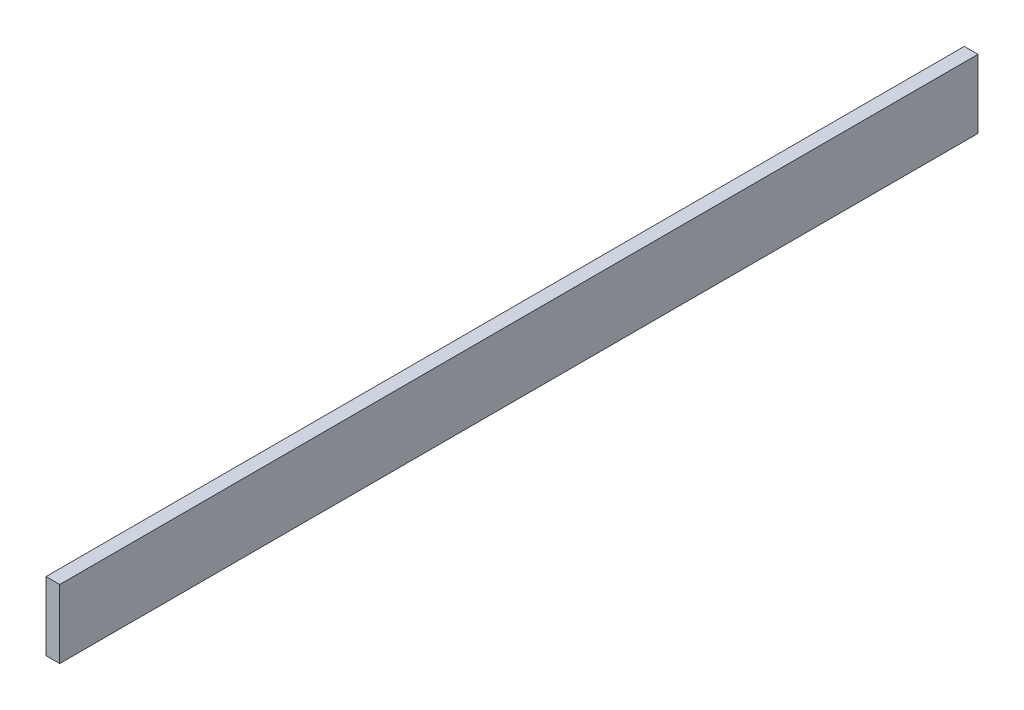
SolidWorks part; units mm, degrees
ref_plane "前视基准面" through (0, 0, 0) normal (0, 0, 1) x (1, 0, 0)
ref_plane "上视基准面" through (0, 0, 0) normal (0, 1, 0) x (1, 0, 0)
ref_plane "右视基准面" through (0, 0, 0) normal (1, 0, 0) x (0, 0, -1)
other "Configuration Table"
sketch "草图1" plane through (0, 0, 0) normal (0, 1, 0) x (1, 0, 0)
  line L0 (12, 2) -> (12, -132)
  line L4 (10, 0) -> (10, -130)
  line L5 (10, -132) -> (12, -132)
  line L7 (10, 2) -> (12, 2)
  line L8 (10, 2) -> (10, -132)
  line L9 (-2, -132) -> (12, -132) construction
  line L10 (-2, 2) -> (-2, -132) construction
  line L11 (0, 0) -> (0, -130) construction
  line L12 (0, -130) -> (10, -130) construction
  line L13 (-2, 2) -> (12, 2) construction
  line L14 (0, 0) -> (10, 0) construction
  dimension "D3" = 130
  dimension "D2" = 2
extrude "凸台-拉伸1" add sketch "草图1" along normal blind 10 contours L7 L8 L4 L5 L0
